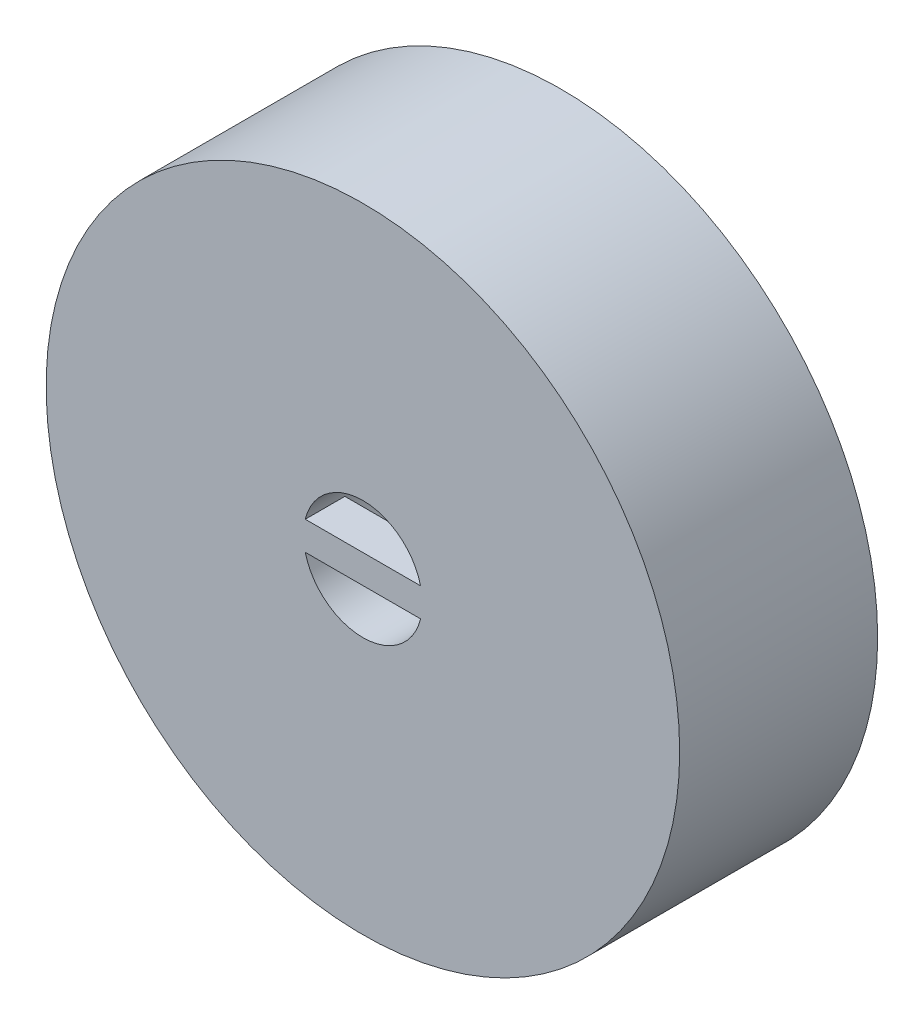
SolidWorks part; units mm, degrees
ref_plane "Front Plane" through (0, 0, 0) normal (0, 0, 1) x (1, 0, 0)
ref_plane "Top Plane" through (0, 0, 0) normal (0, 1, 0) x (1, 0, 0)
ref_plane "Right Plane" through (0, 0, 0) normal (1, 0, 0) x (0, 0, -1)
sketch "Sketch1" plane through (0, 0, 0) normal (0, 0, 1) x (1, 0, 0)
  circle A0 centre (0, 0) radius 1
  dimension "D1" = 2
extrude "Boss-Extrude1" add sketch "Sketch1" along normal blind 1
sketch "Sketch2" plane through (0, 0, 0) normal (0, 0, 1) x (1, 0, 0)
  circle A0 centre (0, 0) radius 0.375
  circle A1 centre (0, 0) radius 1 construction
  circle A2 centre (0, 0) radius 1
  dimension "D1" = 0.75
extrude "Cut-Extrude1" cut sketch "Sketch2" along normal blind 0.375
fillet "Fillet1" radius 0.1 1 edges at (0.375, 0, 0.375)
ref_plane "Plane1" through (0, 0, 1) normal (0, 0, 1) x (1, 0, 0)
sketch "Sketch3" plane through (0, 0, 1) normal (0, 0, 1) x (1, 0, 0)
  line L0 (0, -0.0452) -> (0, 0.0452)
  line L1 (-0.182, 0.0452) -> (0.182, 0.0452)
  line L2 (-0.182, -0.0452) -> (0.182, -0.0452)
  circle A0 centre (0, 0) radius 0.1875
  arc A1 (-0.182, 0.0452) -> (-0.182, -0.0452) centre (0, 0) ccw
  arc A2 (0.182, 0.0452) -> (0.182, -0.0452) centre (0, 0) cw
  arc A3 (-0.182, 0.0452) -> (0.182, 0.0452) centre (0, 0) ccw
  arc A4 (-0.182, 0.0452) -> (0.182, 0.0452) centre (0, 0) cw
  point P6 (0, 0)
  point P9 (0, 0.0452)
  point P12 (0, -0.0452)
  dimension "D1" = 0.375
extrude "Cut-Extrude2" cut sketch "Sketch3" against normal blind 0.125 contours L1 A0 | L2 A0
sketch "Sketch4" plane through (0, 0, 0) normal (0, 0, 1) x (1, 0, 0)
  circle A0 centre (0, 0) radius 0.1875
  dimension "D1" = 0.375
extrude "Cut-Extrude3" cut sketch "Sketch4" along normal blind 0.875 contours A0
